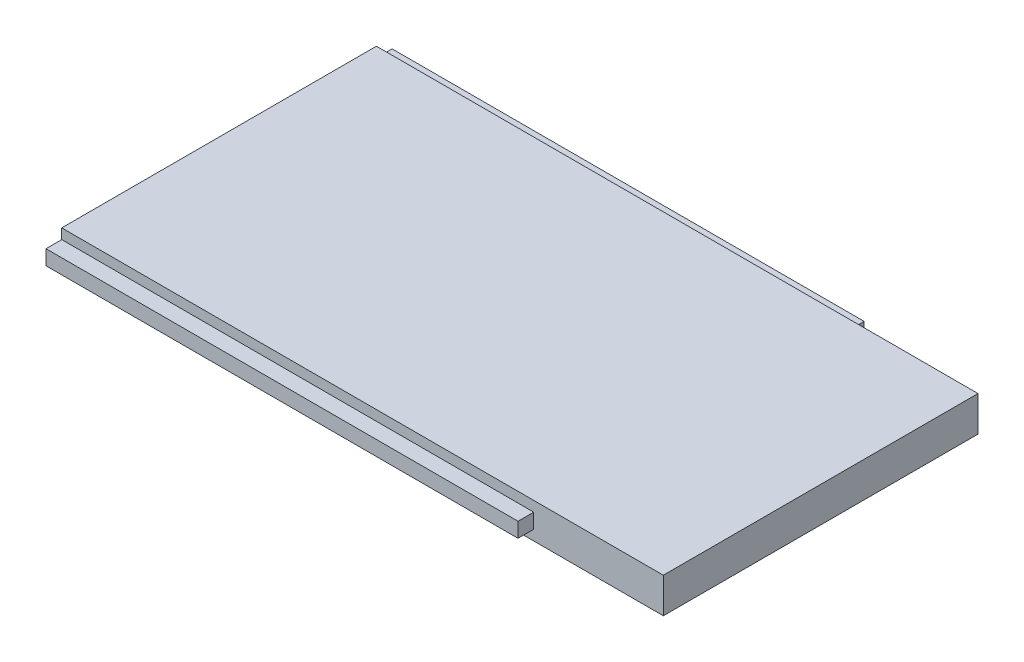
SolidWorks part; units mm, degrees
ref_plane "前视基准面" through (0, 0, 0) normal (0, 0, 1) x (1, 0, 0)
ref_plane "上视基准面" through (0, 0, 0) normal (0, 1, 0) x (1, 0, 0)
ref_plane "右视基准面" through (0, 0, 0) normal (1, 0, 0) x (0, 0, -1)
other "Configuration Table"
sketch "草图1" plane through (0, 0, 0) normal (0, 1, 0) x (1, 0, 0)
  line L1 (0, 0) -> (65, 0)
  line L2 (0, 0) -> (0, 34)
  line L3 (0, 34) -> (65, 34)
  line L4 (65, 0) -> (65, 34)
  dimension "D1" = 65
  dimension "D2" = 34
extrude "凸台-拉伸1" add sketch "草图1" along normal blind 3.8 contours L2 L1 L4 L3
sketch "草图2" plane through (0, 0, -34) normal (0, 0, -1) x (-1, 0, 0)
  line L0 (0, 3.8) -> (0, 0) construction
  line L1 (-51, 2.7) -> (0, 2.7)
  line L2 (-51, 2.7) -> (-51, 1.1)
  line L3 (-51, 1.1) -> (0, 1.1)
  line L4 (0, 2.7) -> (0, 1.1)
  line L5 (0, 3.8) -> (-65, 3.8) construction
  dimension "D1" = 1.6
  dimension "D2" = 51
  dimension "D3" = 1.1
extrude "凸台-拉伸2" add sketch "草图2" along normal blind 1.7
ref_plane "基准面1" through (0, 0, -17) normal (0, 0, 1) x (1, 0, 0)
mirror "镜向1" about plane through (0, 0, -17) normal (0, 0, 1) of "凸台-拉伸2"
